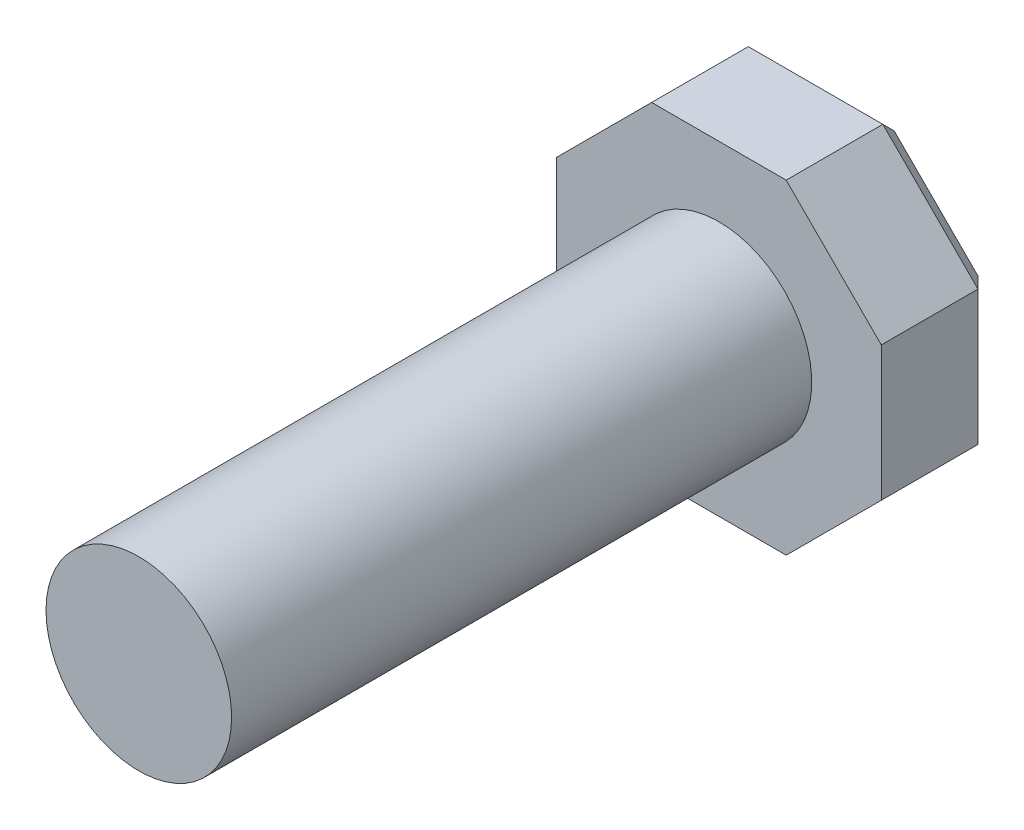
SolidWorks part; units mm, degrees
ref_plane "Front Plane" through (0, 0, 0) normal (0, 0, 1) x (1, 0, 0)
ref_plane "Top Plane" through (0, 0, 0) normal (0, 1, 0) x (1, 0, 0)
ref_plane "Right Plane" through (0, 0, 0) normal (1, 0, 0) x (0, 0, -1)
sketch "Sketch2" plane through (0, 0, 0) normal (0, 0, 1) x (1, 0, 0)
  line L0 (-21, 8.6985) -> (-8.6985, 21)
  line L1 (-8.6985, 21) -> (8.6985, 21)
  line L2 (8.6985, 21) -> (21, 8.6985)
  line L3 (21, 8.6985) -> (21, -8.6985)
  line L4 (21, -8.6985) -> (8.6985, -21)
  line L5 (8.6985, -21) -> (-8.6985, -21)
  line L6 (-8.6985, -21) -> (-21, -8.6985)
  line L7 (-21, -8.6985) -> (-21, 8.6985)
  dimension "D1" = 42
  dimension "D2" = 135
  dimension "D3" = 135
  dimension "D4" = 135
extrude "Extrude2" add sketch "Sketch2" along normal blind 15
chamfer "Chamfer3" distance 2.5 angle 45 8 edges at (-14.8492, 14.8492, 0) (-21, 0, 0) (-14.8492, -14.8492, 0) (0, -21, 0) (14.8492, -14.8492, 0) (21, 0, 0) (14.8492, 14.8492, 0) (0, 21, 0)
sketch "Sketch3" plane through (0, 0, 15) normal (0, 0, 1) x (1, 0, 0)
  circle A0 centre (0, 0) radius 12
extrude "Extrude3" add sketch "Sketch3" along normal blind 75
